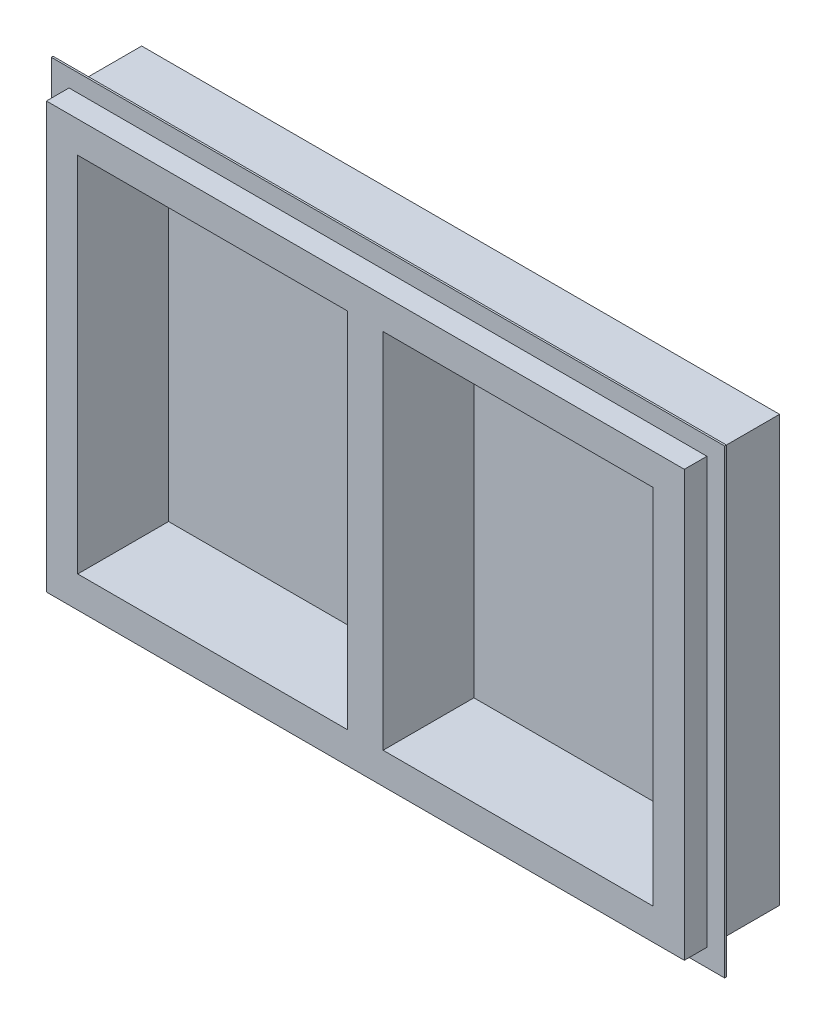
SolidWorks part; units mm, degrees
ref_plane "Front Plane" through (0, 0, 0) normal (0, 0, 1) x (1, 0, 0)
ref_plane "Top Plane" through (0, 0, 0) normal (0, 1, 0) x (1, 0, 0)
ref_plane "Right Plane" through (0, 0, 0) normal (1, 0, 0) x (0, 0, -1)
sketch "Sketch1" plane through (0, 0, 0) normal (0, 0, 1) x (1, 0, 0)
  line L1 (0, 0) -> (914.4, 0)
  line L2 (0, 0) -> (0, 609.6)
  line L3 (0, 609.6) -> (914.4, 609.6)
  line L4 (914.4, 0) -> (914.4, 609.6)
  line L6 (44.9013, 564.6987) -> (869.4987, 564.6987)
  line L7 (869.4987, 564.6987) -> (869.4987, 44.9013)
  line L8 (869.4987, 44.9013) -> (44.9013, 44.9013)
  line L9 (44.9013, 44.9013) -> (44.9013, 564.6987)
extrude "Boss-Extrude1" add sketch "Sketch1" along normal blind 101.6
sketch "Sketch2" plane through (0, 0, 101.6) normal (0, 0, 1) x (1, 0, 0)
  line L1 (0, 635) -> (939.8, 635)
  line L2 (939.8, 635) -> (939.8, -25.4)
  line L3 (939.8, -25.4) -> (-25.4, -25.4)
  line L4 (-25.4, -25.4) -> (-25.4, 635)
  line L5 (-25.4, 635) -> (0, 635)
  line L6 (0, 609.6) -> (914.4, 609.6)
  line L7 (0, 609.6) -> (0, 0)
  line L8 (0, 0) -> (914.4, 0)
  line L9 (914.4, 609.6) -> (914.4, 0)
extrude "Boss-Extrude2" add sketch "Sketch2" along normal blind 2.54 separate body
sketch "Sketch3" plane through (0, 44.9013, 0) normal (0, 1, 0) x (1, 0, 0)
  line L0 (457.2, 0) -> (482.6, 0)
  line L1 (44.9013, 0) -> (869.4987, 0) construction
  line L2 (482.6, 0) -> (482.6, -101.6)
  line L3 (44.9013, -101.6) -> (869.4987, -101.6) construction
  line L4 (482.6, -101.6) -> (431.8, -101.6)
  line L5 (431.8, -101.6) -> (431.8, 0)
  line L6 (431.8, 0) -> (457.2, 0)
extrude "Boss-Extrude3" add sketch "Sketch3" along normal up to next
sketch "Sketch4" plane through (0, 0, 101.6) normal (0, 0, 1) x (1, 0, 0)
  line L1 (44.9013, 564.6987) -> (431.8, 564.6987)
  line L2 (44.9013, 564.6987) -> (44.9013, 44.9013)
  line L3 (44.9013, 44.9013) -> (431.8, 44.9013)
  line L4 (431.8, 564.6987) -> (431.8, 44.9013)
  line L5 (482.6, 44.9013) -> (869.4987, 44.9013)
  line L6 (482.6, 44.9013) -> (482.6, 564.6987)
  line L7 (482.6, 564.6987) -> (869.4987, 564.6987)
  line L8 (869.4987, 44.9013) -> (869.4987, 564.6987)
  line L9 (0, 609.6) -> (914.4, 609.6)
  line L10 (0, 609.6) -> (0, 0)
  line L11 (0, 0) -> (914.4, 0)
  line L12 (914.4, 609.6) -> (914.4, 0)
extrude "Boss-Extrude4" add sketch "Sketch4" along normal blind 34.925
sketch "Sketch5" plane through (0, 0, 0) normal (0, 0, -1) x (-1, 0, 0)
  line L1 (-869.4987, 564.6987) -> (-482.6, 564.6987)
  line L2 (-869.4987, 564.6987) -> (-869.4987, 44.9013)
  line L3 (-869.4987, 44.9013) -> (-482.6, 44.9013)
  line L4 (-482.6, 564.6987) -> (-482.6, 44.9013)
  line L5 (-431.8, 564.6987) -> (-44.9013, 564.6987)
  line L6 (-431.8, 564.6987) -> (-431.8, 44.9013)
  line L7 (-431.8, 44.9013) -> (-44.9013, 44.9013)
  line L8 (-44.9013, 564.6987) -> (-44.9013, 44.9013)
extrude "Boss-Extrude5" add sketch "Sketch5" along normal blind 0.0254 and the other way blind 6.35
